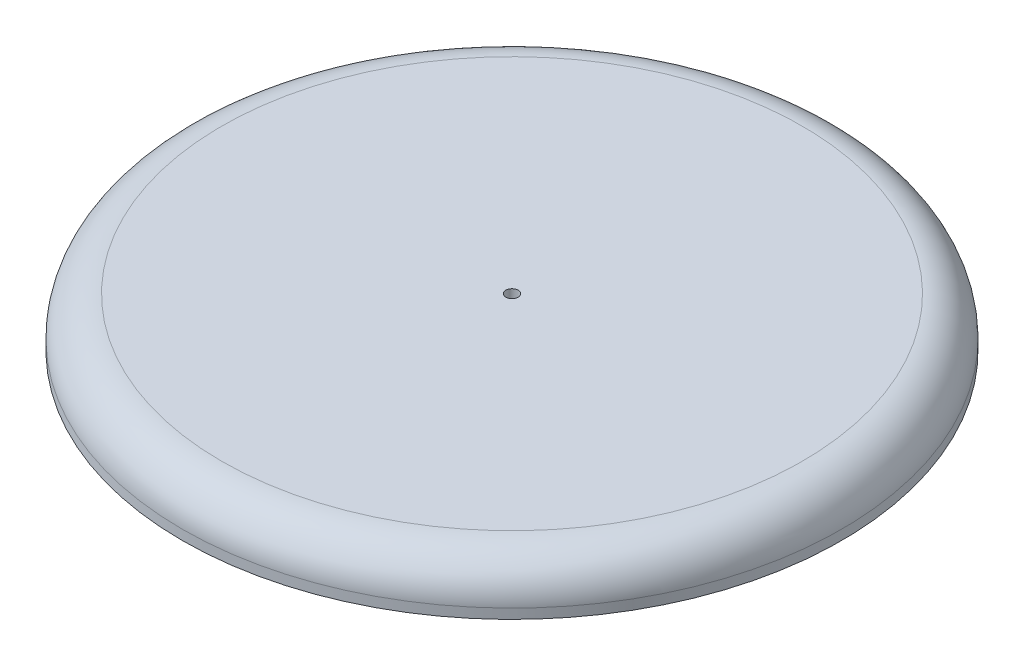
SolidWorks part; units mm, degrees
ref_plane "Front Plane" through (0, 0, 0) normal (0, 0, 1) x (1, 0, 0)
ref_plane "Top Plane" through (0, 0, 0) normal (0, 1, 0) x (1, 0, 0)
ref_plane "Right Plane" through (0, 0, 0) normal (1, 0, 0) x (0, 0, -1)
sketch "Sketch1" plane through (0, 0, 0) normal (0, 1, 0) x (1, 0, 0)
  circle A0 centre (0, 0) radius 67.15
  circle A1 centre (0, 0) radius 30.48
  dimension "D1" = 134.3
  dimension "D2" = 60.96
extrude "Boss-Extrude1" add sketch "Sketch1" along normal blind 10 contours A0
fillet "Fillet1" radius 8 1 edges at (0, 10, 67.15)
sketch "Sketch4" plane through (0, 10, 0) normal (0, 1, 0) x (1, 0, 0)
  circle A0 centre (0, 0) radius 1.25
  dimension "D1" = 2.5
extrude "Cut-Extrude3" cut sketch "Sketch4" against normal up to next
